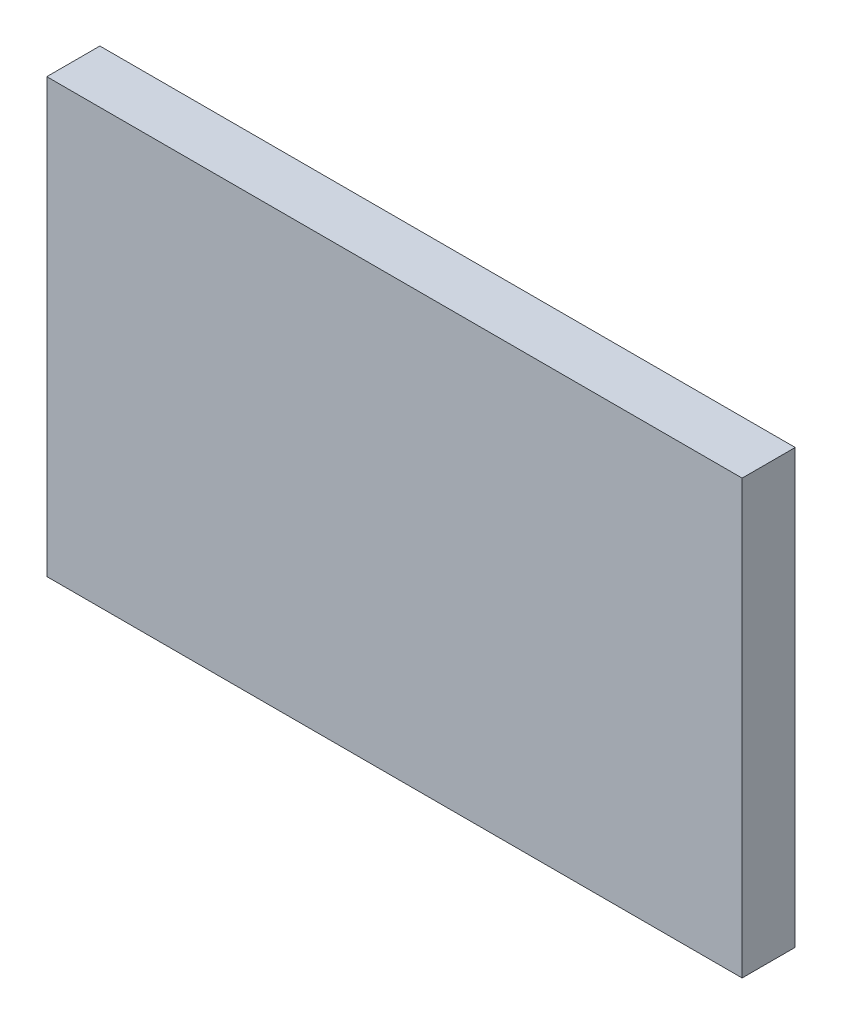
SolidWorks part; units mm, degrees
ref_plane "Ebene vorne" through (0, 0, 0) normal (0, 0, 1) x (1, 0, 0)
ref_plane "Ebene oben" through (0, 0, 0) normal (0, 1, 0) x (1, 0, 0)
ref_plane "Ebene rechts" through (0, 0, 0) normal (1, 0, 0) x (0, 0, -1)
sketch "Skizze1" plane through (0, 0, 0) normal (0, 0, 1) x (1, 0, 0)
  line L1 (-17.693, -5.3339) -> (17.411, -5.3339)
  line L2 (-17.693, -5.3339) -> (-17.693, 16.5221)
  line L3 (-17.693, 16.5221) -> (17.411, 16.5221)
  line L4 (17.411, -5.3339) -> (17.411, 16.5221)
  dimension "D1" = 21.856
  dimension "D2" = 35.104
extrude "Aufsatz-Linear austragen1" add sketch "Skizze1" along normal blind 2.68
